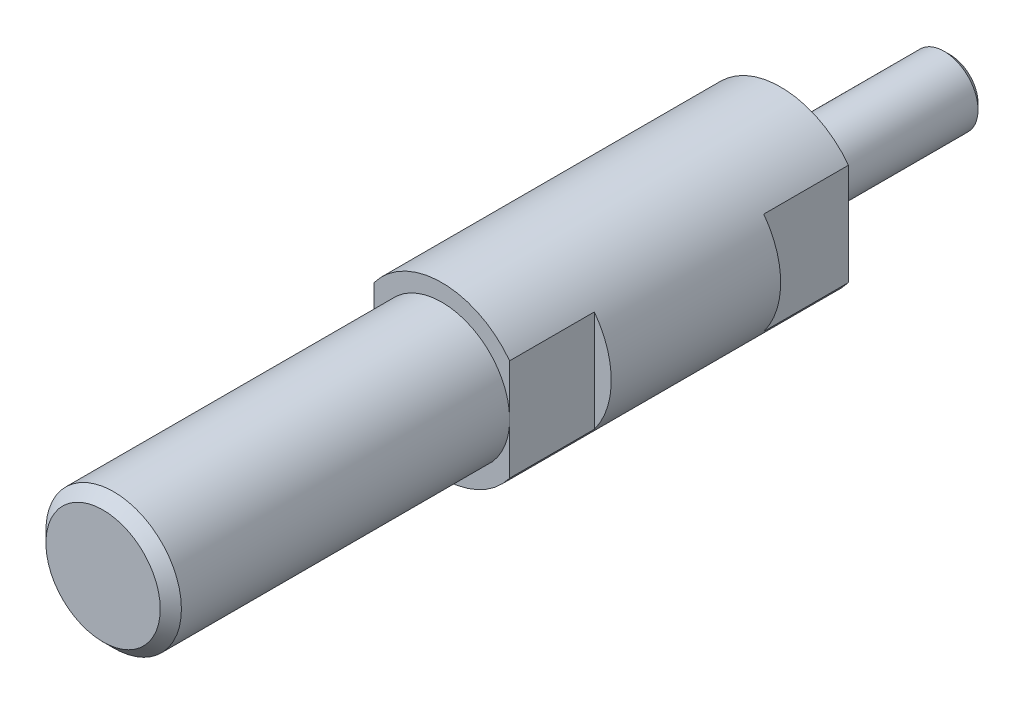
SolidWorks part; units mm, degrees
material "ASTM A36 Aço"
ref_plane "Plano frontal" through (0, 0, 0) normal (0, 0, 1) x (1, 0, 0)
ref_plane "Plano superior" through (0, 0, 0) normal (0, 1, 0) x (1, 0, 0)
ref_plane "Plano direito" through (0, 0, 0) normal (1, 0, 0) x (0, 0, -1)
sketch "Esboço2" plane through (0, 0, 0) normal (0, 0, 1) x (1, 0, 0)
  circle A0 centre (0, 0) radius 5
  dimension "D1" = 10
extrude "Ressalto-extrusão1" add sketch "Esboço2" against normal blind 20
sketch "Esboço3" plane through (0, 0, 0) normal (0, 0, 1) x (1, 0, 0)
  circle A0 centre (0, 0) radius 4
  dimension "D1" = 8
extrude "Ressalto-extrusão2" add sketch "Esboço3" along normal blind 20
sketch "Esboço4" plane through (0, 0, -20) normal (0, 0, -1) x (-1, 0, 0)
  circle A0 centre (0, 0) radius 2
  dimension "D1" = 4
extrude "Ressalto-extrusão3" add sketch "Esboço4" along normal blind 10
chamfer "Chanfro1" distance 0.625 angle 45 1 edges at (4, 0, 20)
cosmetic thread "Representação de rosca12" parameters "D1"=20, "D2"=6.619
chamfer "Chanfro2" distance 0.35 angle 45 1 edges at (-2, 0, -30)
cosmetic thread "Representação de rosca11" parameters "D1"=10, "D2"=3.22
sketch "Esboço6" plane through (0, 0, 0) normal (0, 1, 0) x (1, 0, 0)
  line L6 (-5, 15) -> (-4, 15)
  line L8 (-4, 15) -> (-4, 20)
  line L10 (-4, 20) -> (-5, 20)
  line L11 (-5, 20) -> (-5, 15)
  line L23 (5, 20) -> (-5, 20) construction
  line L25 (-5, 20) -> (-5, 0) construction
  line L26 (-5, 10) -> (5, 10) construction
  line L27 (5, 0) -> (5, 20) construction
  line L28 (-4, 0) -> (-5, 0)
  line L29 (-5, 0) -> (-5, 5)
  line L30 (-5, 5) -> (-4, 5)
  line L31 (-4, 5) -> (-4, 0)
  line L32 (0, 0) -> (0, 20) construction
  line L33 (4, 20) -> (5, 20)
  line L34 (5, 20) -> (5, 15)
  line L35 (4, 15) -> (4, 20)
  line L36 (5, 15) -> (4, 15)
  line L37 (5, 5) -> (4, 5)
  line L38 (5, 0) -> (5, 5)
  line L39 (4, 0) -> (5, 0)
  line L40 (4, 5) -> (4, 0)
  dimension "D1" = 5
  dimension "D2" = 1
extrude "Corte-extrusão2" cut sketch "Esboço6" against normal through all both and the other way through all
